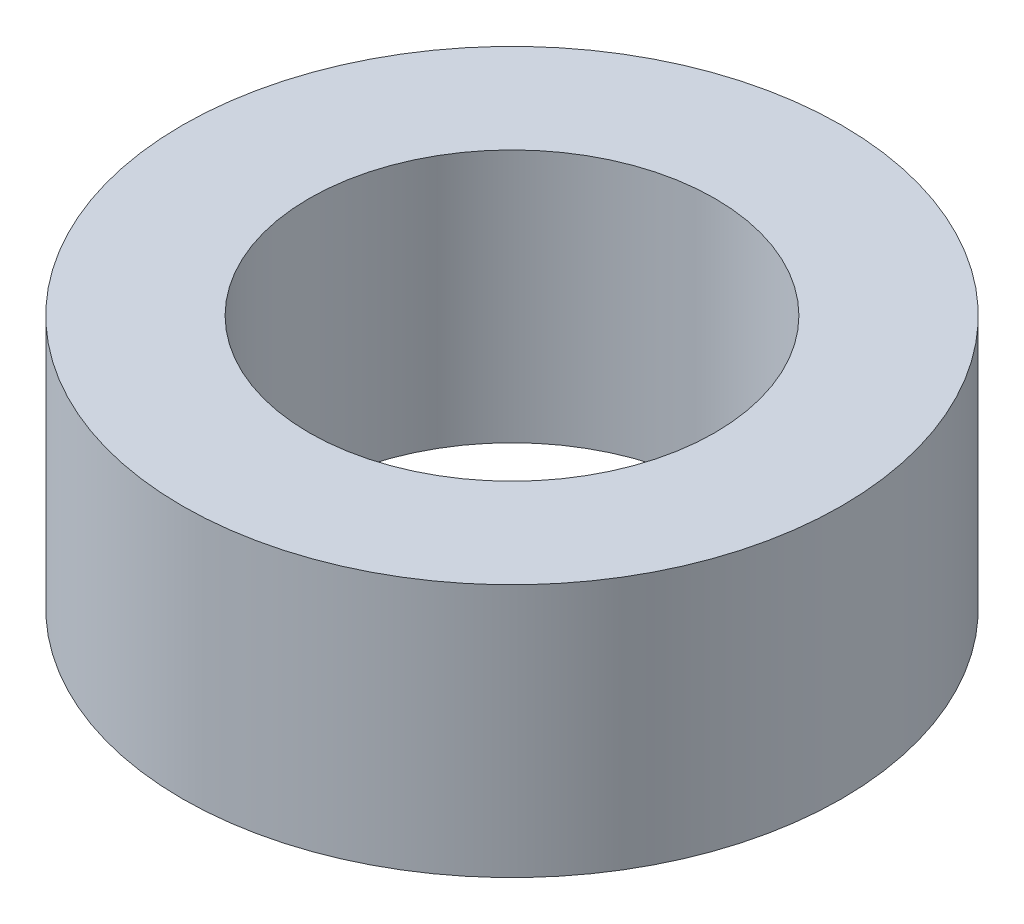
SolidWorks part; units mm, degrees
ref_plane "前视基准面" through (0, 0, 0) normal (0, 0, 1) x (1, 0, 0)
ref_plane "上视基准面" through (0, 0, 0) normal (0, 1, 0) x (1, 0, 0)
ref_plane "右视基准面" through (0, 0, 0) normal (1, 0, 0) x (0, 0, -1)
other "Configuration Table"
sketch "草图1" plane through (0, 0, 0) normal (0, 1, 0) x (1, 0, 0)
  circle A0 centre (0, 0) radius 6.5
  circle A1 centre (0, 0) radius 4
  dimension "D1" = 8
  dimension "D2" = 13
extrude "凸台-拉伸1" add sketch "草图1" along normal blind 5
